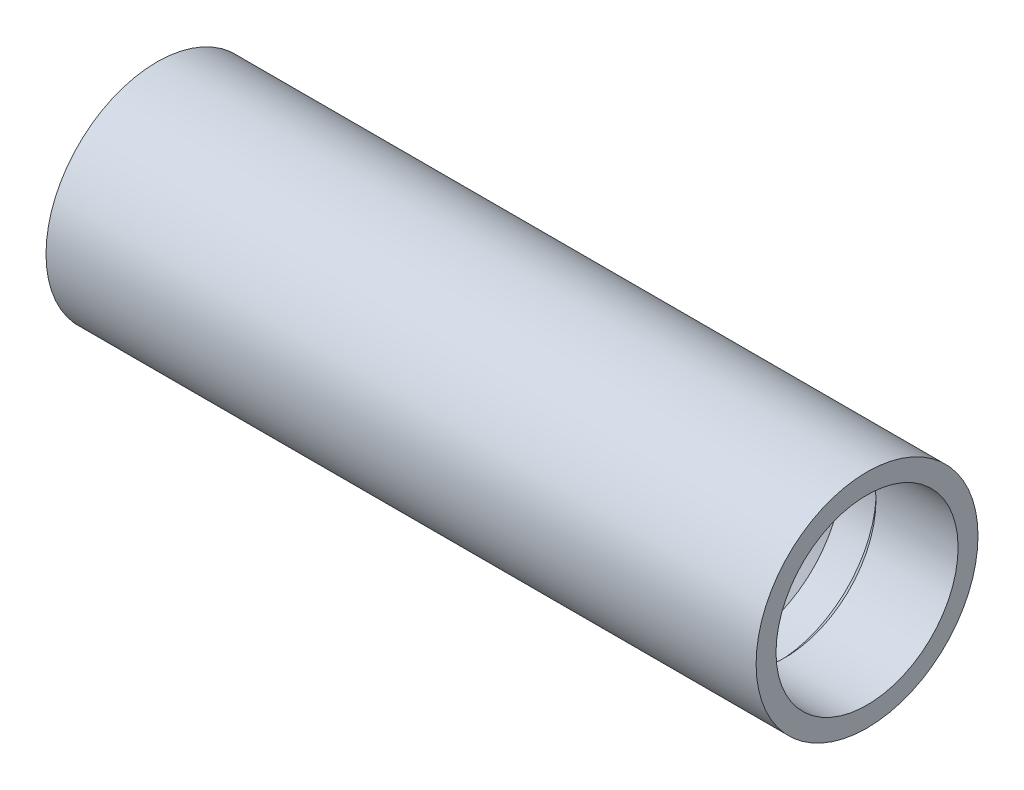
SolidWorks part; units mm, degrees
material "Brass"
ref_plane "Front Plane" through (0, 0, 0) normal (0, 0, 1) x (1, 0, 0)
ref_plane "Top Plane" through (0, 0, 0) normal (0, 1, 0) x (1, 0, 0)
ref_plane "Right Plane" through (0, 0, 0) normal (1, 0, 0) x (0, 0, -1)
sketch "Sketch1" plane through (0, 0, 0) normal (1, 0, 0) x (0, 0, -1)
  circle A0 centre (0, 0) radius 4.5593
  circle A1 centre (0, 0) radius 5.5562
  dimension "D1" = 11.1125
  dimension "D2" = 9.1186
extrude "Boss-Extrude1" add sketch "Sketch1" along normal blind 35.56
sketch "Sketch2" plane through (0, 0, 0) normal (0, 0, 1) x (1, 0, 0)
  line L0 (0, 0) -> (35.7057, 0) construction
  line L1 (17.5702, -4.445) -> (20.0335, -4.445)
  line L2 (20.0335, -4.445) -> (19.5832, -4.976)
  line L3 (19.5832, -4.976) -> (18.0206, -4.976)
  line L4 (18.0206, -4.976) -> (17.5702, -4.445)
  line L5 (1.691, -4.445) -> (32.7103, -4.445) construction
  line L6 (18.8019, -4.445) -> (18.8019, -6.8532) construction
  line L7 (28.7745, -4.445) -> (31.5592, -4.445)
  line L8 (31.5592, -4.445) -> (31.0205, -5.0049)
  line L9 (31.0205, -5.0049) -> (29.3131, -5.0049)
  line L10 (29.3131, -5.0049) -> (28.7745, -4.445)
  line L11 (30.1668, -4.445) -> (30.1668, -7.0853) construction
  line L16 (4.1827, -4.445) -> (7.5571, -4.445)
  line L17 (7.5571, -4.445) -> (7.1067, -5.1802)
  line L18 (7.1067, -5.1802) -> (4.633, -5.1802)
  line L19 (4.633, -5.1802) -> (4.1827, -4.445)
  line L20 (5.8699, -4.445) -> (5.8699, -6.8532) construction
  point P11 (19.5832, -4.976)
  point P18 (30.8113, -5.0819)
  point P19 (31.0205, -5.0049)
  point P26 (4.1827, -4.5641)
  point P27 (0, 0)
  dimension "D1" = 4.445
revolve "Cut-Revolve1" cut sketch "Sketch2" angle 360 about L0
